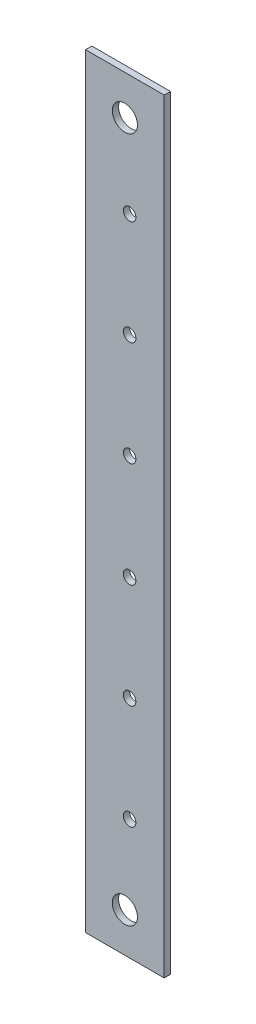
SolidWorks part; units mm, degrees
ref_plane "Front Plane" through (0, 0, 0) normal (0, 0, 1) x (1, 0, 0)
ref_plane "Top Plane" through (0, 0, 0) normal (0, 1, 0) x (1, 0, 0)
ref_plane "Right Plane" through (0, 0, 0) normal (1, 0, 0) x (0, 0, -1)
sketch "Sketch1" plane through (0, 0, 0) normal (0, 0, 1) x (1, 0, 0)
  line L0 (-12.5, 0) -> (12.5, 0) construction
  line L1 (3.5, 121.5) -> (12.5, 121.5)
  line L2 (-12.5, 112.5) -> (-12.5, -105.5)
  line L3 (3.5, -121.5) -> (12.5, -121.5)
  line L4 (12.5, 121.5) -> (12.5, -121.5)
  line L5 (-12.5, 121.5) -> (12.5, -121.5) construction
  line L6 (-12.5, -121.5) -> (12.5, 121.5) construction
  line L7 (-12.5, 112.5) -> (-12.5, 121.5) construction
  line L8 (-12.5, 121.5) -> (3.5, 121.5) construction
  line L9 (-12.5, 112.5) -> (-12.5, 121.5) construction
  line L12 (3.5, -121.5) -> (0, -121.5)
  line L13 (-12.5, -105.5) -> (-12.5, -115.4875)
  line L14 (-12.5, 112.5) -> (-12.5, 121.5)
  line L15 (-12.5, 121.5) -> (3.5, 121.5)
  line L16 (-12.5, -115.4875) -> (-12.5, -121.5)
  line L17 (-12.5, -121.5) -> (0, -121.5)
  circle A0 centre (0, 109) radius 4
  circle A1 centre (0, -109) radius 4
  point P0 (0, 0)
  dimension "D4" = 8
  dimension "D1" = 25
  dimension "D3" = 218
  dimension "D6" = 243
extrude "Boss-Extrude1" add sketch "Sketch1" along normal blind 2
sketch "Sketch2" plane through (0, 0, 2) normal (0, 0, 1) x (1, 0, 0)
  circle A0 centre (1.5, 83.3) radius 2
  circle A1 centre (1.5, 50) radius 2
  circle A2 centre (1.5, 16.7) radius 2
  circle A3 centre (1.5, -16.7) radius 2
  circle A4 centre (1.5, -50) radius 2
  circle A5 centre (1.5, -83.3) radius 2
extrude "Cut-Extrude1" cut sketch "Sketch2" against normal blind 2
